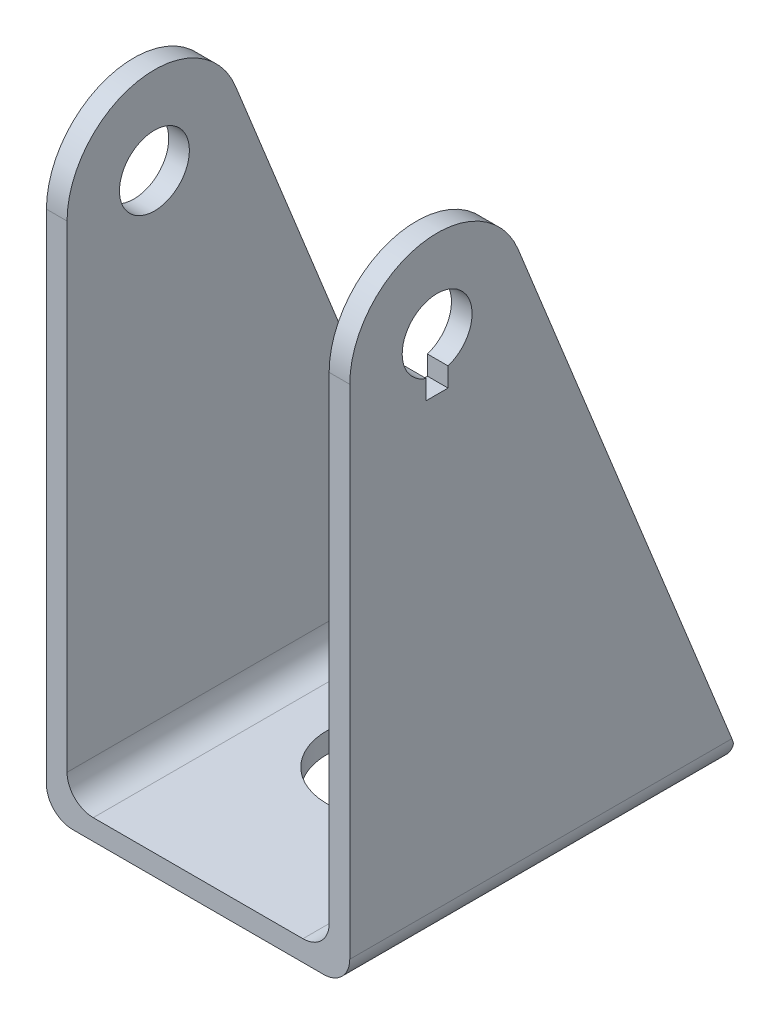
SolidWorks part; units mm, degrees
ref_plane "Alzado" through (0, 0, 0) normal (0, 0, 1) x (1, 0, 0)
ref_plane "Planta" through (0, 0, 0) normal (0, 1, 0) x (1, 0, 0)
ref_plane "Vista lateral" through (0, 0, 0) normal (1, 0, 0) x (0, 0, -1)
sketch "Croquis1" plane through (0, 0, 0) normal (1, 0, 0) x (0, 0, -1)
  line L0 (0, 60) -> (0, 0)
  line L1 (0, 0) -> (44, 0)
  line L2 (44, 0) -> (44, 2.36)
  line L3 (44, 2.36) -> (19.2757, 63.7365)
  arc A0 (19.2757, 63.7365) -> (0, 60) centre (10, 60) ccw
  circle A1 centre (10, 60) radius 4
  dimension "D1" = 10
  dimension "D2" = 8
  dimension "D3" = 44
  dimension "D4" = 60
  dimension "D5" = 2.36
extrude "Saliente-Extruir1" add sketch "Croquis1" along normal blind 34.72
sketch "Croquis2" plane through (0, 0, 0) normal (0, 0, 1) x (1, 0, 0)
  line L0 (34.72, 70) -> (0, 70) construction
  line L1 (2.36, 70) -> (32.36, 70)
  line L2 (2.36, 70) -> (2.36, 2.36)
  line L3 (2.36, 2.36) -> (32.36, 2.36)
  line L4 (32.36, 70) -> (32.36, 2.36)
  line L5 (34.72, 60) -> (0, 60) construction
  line L6 (34.72, 0) -> (0, 0) construction
  point P6 (17.36, 2.36)
  point P9 (17.36, 60)
  dimension "D1" = 30
  dimension "D2" = 2.36
extrude "Cortar-Extruir1" cut sketch "Croquis2" against normal through all
fillet "Redondeo1" radius 3 4 edges at (34.72, 0, -22) (0, 0, -22) (32.36, 2.36, -22) (2.36, 2.36, -22)
sketch "Croquis3" plane through (32.36, 0, 0) normal (-1, 0, 0) x (0, 0, 1)
  line L1 (-8.75, 60.8122) -> (-11.25, 60.8122)
  line L2 (-8.75, 56.2003) -> (-8.75, 54)
  line L3 (-8.75, 54) -> (-11.25, 54)
  line L4 (-11.25, 56.2003) -> (-11.25, 54)
  circle A0 centre (-10, 60) radius 4 construction
  arc A1 (-11.25, 56.2003) -> (-8.75, 56.2003) centre (-10, 60) ccw
  point P8 (-10, 60.8122)
  circle M2 centre (-10, 60) radius 4
  dimension "D1" = 6
  dimension "D2" = 2.5
extrude "Cortar-Extruir2" cut sketch "Croquis3" against normal through all contours L4 L3 L2 M2
sketch "Croquis4" plane through (0, 2.36, 0) normal (0, 1, 0) x (1, 0, 0)
  line L0 (5.36, 0) -> (29.36, 0) construction
  line L1 (2.36, 0) -> (2.36, 19.2757) construction
  circle A0 centre (17.36, 22) radius 7.25
  dimension "D1" = 14.5
  dimension "D2" = 22
  dimension "D3" = 15
extrude "Cortar-Extruir3" cut sketch "Croquis4" against normal through all
